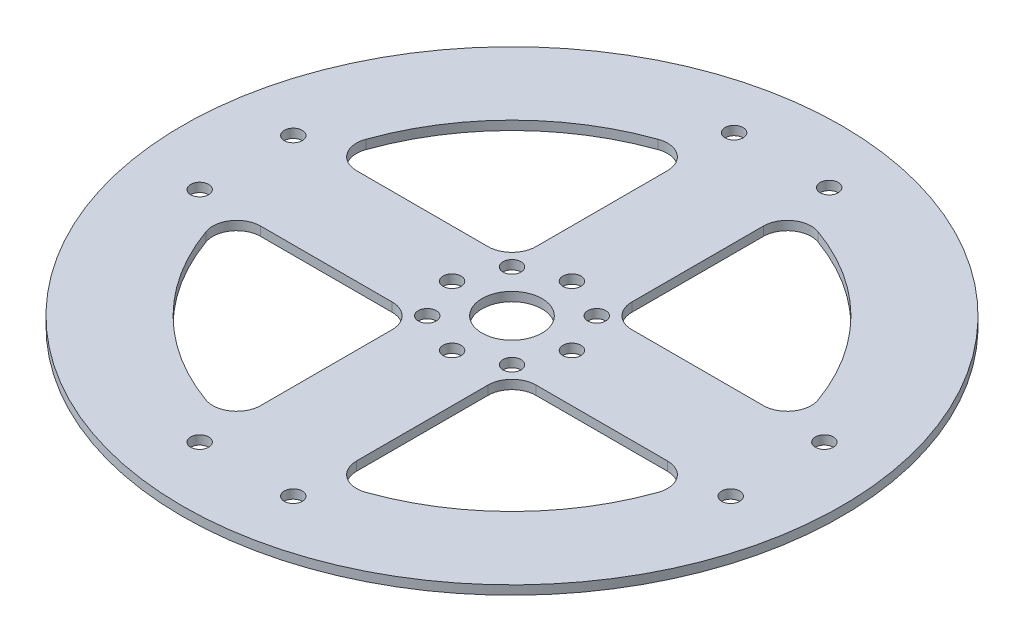
SolidWorks part; units mm, degrees
material "Thornel Mat VMA"
ref_plane "Front Plane" through (0, 0, 0) normal (0, 0, 1) x (1, 0, 0)
ref_plane "Top Plane" through (0, 0, 0) normal (0, 1, 0) x (1, 0, 0)
ref_plane "Right Plane" through (0, 0, 0) normal (1, 0, 0) x (0, 0, -1)
sketch "Sketch1" plane through (0, 0, 0) normal (0, 1, 0) x (1, 0, 0)
  line L0 (0, 55) -> (0, -55) construction
  line L1 (55, 0) -> (-55, 0) construction
  line L2 (8, 33.9411) -> (8, 12)
  line L3 (-33.9411, 8) -> (-12, 8)
  line L4 (-33.9411, -8) -> (-12, -8)
  line L5 (-8, 33.9411) -> (-8, 12)
  line L6 (12, 8) -> (33.9411, 8)
  line L7 (-8, -12) -> (-8, -33.9411)
  line L8 (12, -8) -> (33.9411, -8)
  line L9 (8, -12) -> (8, -33.9411)
  circle A0 centre (0, 0) radius 55
  arc A1 (-13.3333, 37.7124) -> (-37.7124, 13.3333) centre (0, 0) ccw
  circle A2 centre (0, 0) radius 5
  arc A3 (13.3333, -37.7124) -> (37.7124, -13.3333) centre (0, 0) ccw
  arc A4 (37.7124, 13.3333) -> (13.3333, 37.7124) centre (0, 0) ccw
  arc A5 (-37.7124, -13.3333) -> (-13.3333, -37.7124) centre (0, 0) ccw
  arc A6 (33.9411, 8) -> (37.7124, 13.3333) centre (33.9411, 12) ccw
  arc A7 (13.3333, 37.7124) -> (8, 33.9411) centre (12, 33.9411) ccw
  arc A8 (8, 12) -> (12, 8) centre (12, 12) ccw
  arc A9 (8, -33.9411) -> (13.3333, -37.7124) centre (12, -33.9411) ccw
  arc A10 (37.7124, -13.3333) -> (33.9411, -8) centre (33.9411, -12) ccw
  arc A11 (12, -8) -> (8, -12) centre (12, -12) ccw
  arc A12 (-8, -12) -> (-12, -8) centre (-12, -12) ccw
  arc A13 (-8, -33.9411) -> (-13.3333, -37.7124) centre (-12, -33.9411) cw
  arc A14 (-37.7124, -13.3333) -> (-33.9411, -8) centre (-33.9411, -12) cw
  arc A15 (-13.3333, 37.7124) -> (-8, 33.9411) centre (-12, 33.9411) cw
  arc A16 (-8, 12) -> (-12, 8) centre (-12, 12) cw
  arc A17 (-33.9411, 8) -> (-37.7124, 13.3333) centre (-33.9411, 12) cw
  point P22 (39.1918, 8)
  point P29 (8, -39.1918)
  point P32 (39.1918, -8)
  point P35 (8, -8)
  point P42 (-39.1918, -8)
  dimension "D1" = 110
  dimension "D2" = 80
  dimension "D3" = 10
  dimension "D8" = 4
  dimension "D4" = 8
  dimension "D5" = 8
  dimension "D6" = 8
  dimension "D7" = 8
extrude "Boss-Extrude1" add sketch "Sketch1" against normal blind 1.5
sketch "Sketch2" plane through (0, 0, 0) normal (0, 1, 0) x (1, 0, 0)
  line L0 (0, 0) -> (-44.3163, 7.8142) construction
  line L1 (0, 0) -> (10, 0) construction
  line L2 (0, 0) -> (7.0711, -7.0711) construction
  line L3 (0, 0) -> (0, -10) construction
  line L4 (0, 0) -> (-7.0711, -7.0711) construction
  line L5 (0, 0) -> (-10, 0) construction
  line L6 (0, 0) -> (-7.0711, 7.0711) construction
  line L7 (0, 0) -> (0, 10) construction
  line L8 (0, 0) -> (7.0711, 7.0711) construction
  line L9 (0, 0) -> (-44.3163, -7.8142) construction
  line L10 (0, 0) -> (-7.9347, 45) construction
  line L11 (0, 0) -> (-45, 0) construction
  line L13 (0, 0) -> (0, 45.0157) construction
  line L14 (0, 0) -> (7.9347, 45) construction
  line L15 (0, 0) -> (44.3163, 7.8142) construction
  line L16 (0, 0) -> (35, 0) construction
  line L17 (0, 0) -> (44.3163, -7.8142) construction
  line L18 (0, 0) -> (7.8142, -44.3163) construction
  line L19 (0, 0) -> (0, -35) construction
  line L20 (0, 0) -> (-7.8142, -44.3163) construction
  circle A2 centre (10, 0) radius 1.5
  circle A3 centre (7.0711, -7.0711) radius 1.5
  circle A4 centre (0, -10) radius 1.5
  circle A5 centre (-7.0711, -7.0711) radius 1.5
  circle A6 centre (-10, 0) radius 1.5
  circle A7 centre (-7.0711, 7.0711) radius 1.5
  circle A8 centre (0, 10) radius 1.5
  circle A9 centre (7.0711, 7.0711) radius 1.5
  circle A16 centre (-44.3163, 7.8142) radius 1.5
  circle A17 centre (-44.3163, -7.8142) radius 1.5
  circle A18 centre (7.9347, 45) radius 1.5
  circle A19 centre (-7.9347, 45) radius 1.5
  circle A20 centre (44.3163, -7.8142) radius 1.5
  circle A21 centre (44.3163, 7.8142) radius 1.5
  circle A22 centre (-7.8142, -44.3163) radius 1.5
  circle A23 centre (7.8142, -44.3163) radius 1.5
  point P24 (0, 0)
  point P38 (0, 0)
  point P45 (0, 0)
  dimension "D2" = 45
  dimension "D3" = 10
  dimension "D6" = 3
  dimension "D4" = 3
  dimension "D1" = 45
  dimension "D5" = 10
  dimension "D8" = 45
  dimension "D9" = 45
  dimension "D10" = 10
  dimension "D11" = 90
  dimension "D12" = 10
  dimension "D13" = 90
  dimension "D14" = 45
  dimension "D15" = 45
  dimension "D16" = 10
  dimension "D17" = 10
  dimension "D18" = 90
  dimension "D19" = 10
  dimension "D20" = 10
  dimension "D21" = 45
  dimension "D22" = 45
  dimension "D7" = 8
extrude "Cut-Extrude1" cut sketch "Sketch2" against normal blind 1.5
